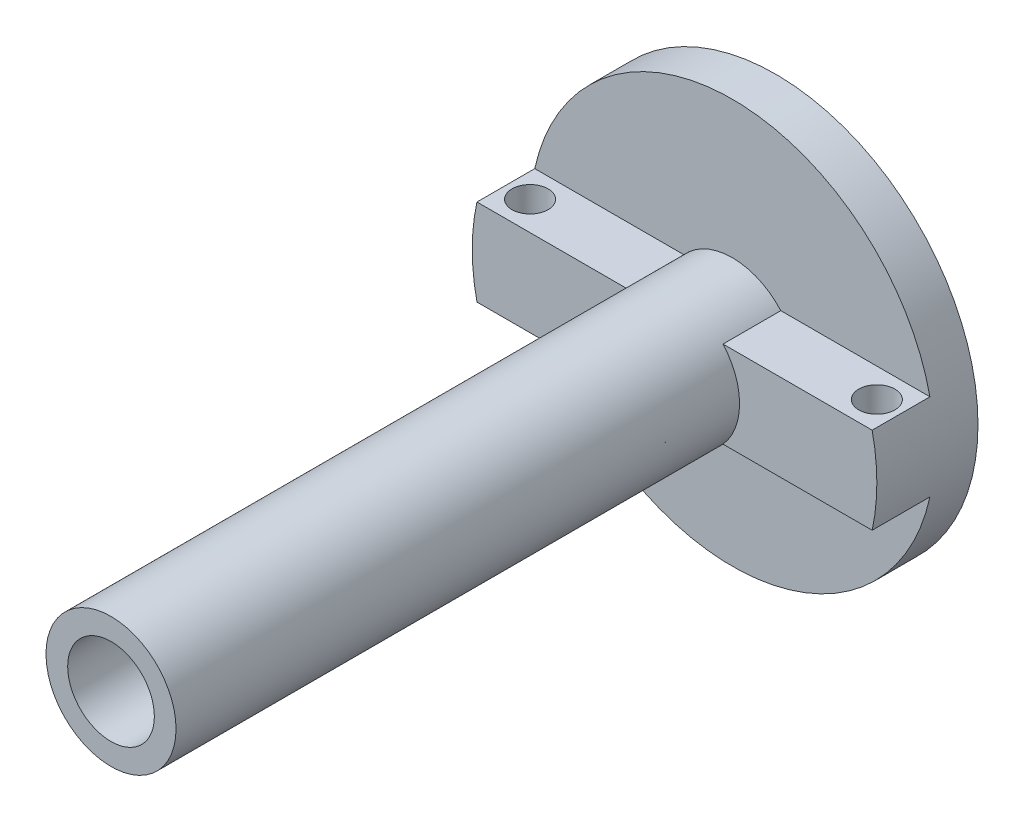
SolidWorks part; units mm, degrees
ref_plane "Front Plane" through (0, 0, 0) normal (0, 0, 1) x (1, 0, 0)
ref_plane "Top Plane" through (0, 0, 0) normal (0, 1, 0) x (1, 0, 0)
ref_plane "Right Plane" through (0, 0, 0) normal (1, 0, 0) x (0, 0, -1)
sketch "Sketch1" plane through (0, 0, 0) normal (0, 0, 1) x (1, 0, 0)
  circle A0 centre (0, 0) radius 7
  dimension "D1" = 14
extrude "Boss-Extrude1" add sketch "Sketch1" along normal blind 1.5
sketch "Sketch2" plane through (0, 0, 1.5) normal (0, 0, 1) x (1, 0, 0)
  circle A0 centre (0, 0) radius 2.25
  dimension "D1" = 4.5
extrude "Boss-Extrude2" add sketch "Sketch2" along normal blind 21.5
sketch "Sketch4" plane through (0, 0, 0) normal (0, 0, -1) x (-1, 0, 0)
  circle A0 centre (0, 0) radius 1.5
  dimension "D1" = 3
extrude "Cut-Extrude1" cut sketch "Sketch4" against normal up to next
sketch "Sketch15" plane through (0, 0, 1.5) normal (0, 0, 1) x (1, 0, 0)
  line L1 (6.8374, -1.5) -> (-6.8374, -1.5)
  line L3 (6.8374, 1.5) -> (-6.8374, 1.5)
  line L5 (6.8374, -1.5) -> (-6.8374, 1.5) construction
  line L6 (6.8374, 1.5) -> (-6.8374, -1.5) construction
  arc A0 (6.8374, -1.5) -> (6.8374, 1.5) centre (0, 0) ccw
  circle A1 centre (0, 0) radius 7 construction
  arc A2 (-6.8374, 1.5) -> (-6.8374, -1.5) centre (0, 0) ccw
  point P0 (0, 0)
  dimension "D1" = 3
extrude "Boss-Extrude5" add sketch "Sketch15" along normal blind 2
sketch "Sketch16" plane through (0, -1.5, 0) normal (0, -1, 0) x (1, 0, 0)
  line L0 (-6.8374, 1.5) -> (-1.6771, 1.5) construction
  line L1 (0, 0) -> (0, 18.3725) construction
  circle A0 centre (-6, 2.5) radius 0.625
  circle A1 centre (6, 2.5) radius 0.625
  dimension "D1" = 1.25
  dimension "D2" = 6
  dimension "D3" = 1
extrude "Cut-Extrude5" cut sketch "Sketch16" against normal up to next
sketch "Sketch17" plane through (0, 0, 1.5) normal (0, 0, -1) x (-1, 0, 0)
  circle A0 centre (0, 0) radius 1.5
extrude "Cut-Extrude6" cut sketch "Sketch17" against normal up to next
equation "\"15.5.000000mm\"=14"
